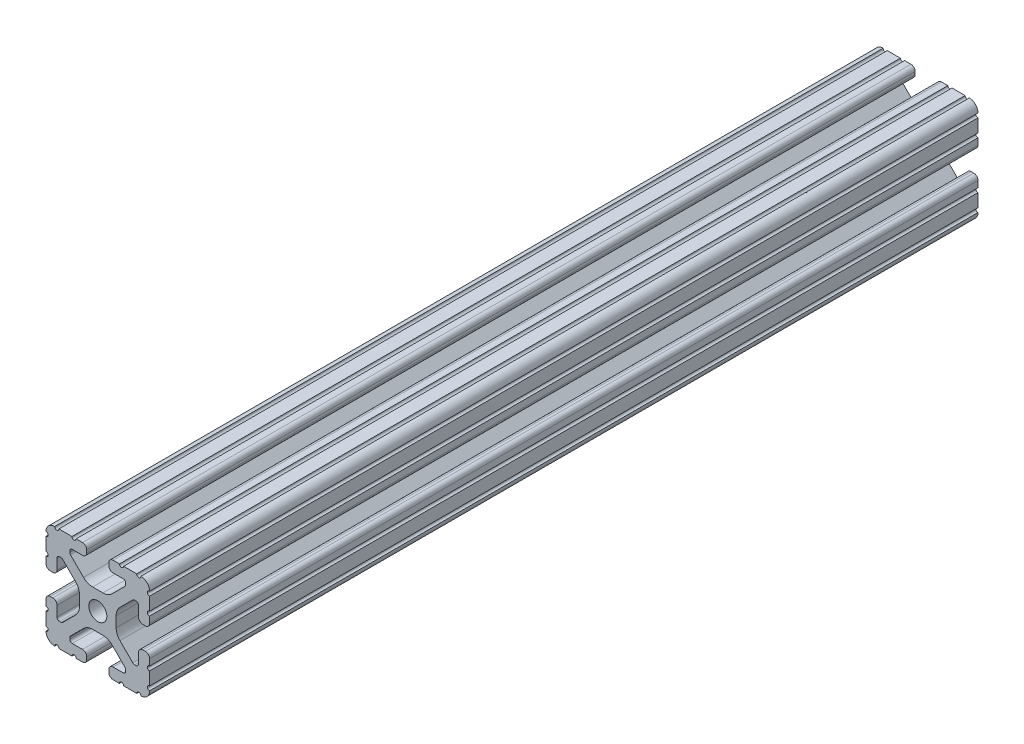
SolidWorks part; units mm, degrees
ref_plane "Front Plane" through (0, 0, 0) normal (0, 0, 1) x (1, 0, 0)
ref_plane "Top Plane" through (0, 0, 0) normal (0, 1, 0) x (1, 0, 0)
ref_plane "Right Plane" through (0, 0, 0) normal (1, 0, 0) x (0, 0, -1)
sketch "Sketch1" plane through (0, 0, 0) normal (0, 0, 1) x (1, 0, 0)
  line L0 (-10.287, 13.5524) -> (-10.287, 14.0843)
  line L1 (-9.3853, 14.986) -> (-5.6176, 14.986)
  line L2 (-4.064, 16.5396) -> (-4.064, 17.4964)
  line L3 (-5.6176, 19.05) -> (-7.9742, 19.05)
  line L4 (-9.4982, 19.05) -> (-14.3277, 19.05)
  line L5 (-19.05, 14.3277) -> (-19.05, 9.4961)
  line L6 (-19.05, 7.9763) -> (-19.05, 5.6176)
  line L7 (-17.4964, 4.064) -> (-16.5396, 4.064)
  line L8 (-14.986, 5.6176) -> (-14.986, 9.3853)
  line L9 (-14.0843, 10.287) -> (-13.516, 10.287)
  line L10 (-12.8784, 10.0229) -> (-8.1476, 5.2921)
  line L11 (-6.7564, 1.9335) -> (-6.7564, -1.9335)
  line L12 (-8.1476, -5.2921) -> (-12.8784, -10.0229)
  line L13 (-13.516, -10.287) -> (-14.0843, -10.287)
  line L14 (-14.986, -9.3853) -> (-14.986, -5.6176)
  line L15 (-16.5396, -4.064) -> (-17.4964, -4.064)
  line L16 (-19.05, -5.6176) -> (-19.05, -7.9763)
  line L17 (-19.05, -9.4961) -> (-19.05, -14.3277)
  line L18 (-14.3277, -19.05) -> (-9.4961, -19.05)
  line L19 (-7.9763, -19.05) -> (-5.6176, -19.05)
  line L20 (-4.064, -17.4964) -> (-4.064, -16.5396)
  line L21 (-5.6176, -14.986) -> (-9.3853, -14.986)
  line L22 (-10.287, -14.0843) -> (-10.287, -13.5524)
  line L23 (-10.0229, -12.9148) -> (-5.2522, -8.144)
  line L24 (-1.9022, -6.7564) -> (1.9022, -6.7564)
  line L25 (5.2522, -8.144) -> (10.0229, -12.9148)
  line L26 (10.287, -13.5524) -> (10.287, -14.0843)
  line L27 (9.3853, -14.986) -> (5.6176, -14.986)
  line L28 (4.064, -16.5396) -> (4.064, -17.4964)
  line L29 (5.6176, -19.05) -> (7.9763, -19.05)
  line L30 (9.4961, -19.05) -> (14.3277, -19.05)
  line L31 (19.05, -14.3277) -> (19.05, -9.4961)
  line L32 (19.05, -7.9763) -> (19.05, -5.6176)
  line L33 (17.4964, -4.064) -> (16.5396, -4.064)
  line L34 (14.986, -5.6176) -> (14.986, -9.3853)
  line L35 (14.0843, -10.287) -> (13.516, -10.287)
  line L36 (12.8784, -10.0229) -> (8.1476, -5.2921)
  line L37 (6.7564, -1.9335) -> (6.7564, 1.9335)
  line L38 (8.1476, 5.2921) -> (12.8784, 10.0229)
  line L39 (13.516, 10.287) -> (14.0843, 10.287)
  line L40 (14.986, 9.3853) -> (14.986, 5.6176)
  line L41 (16.5396, 4.064) -> (17.4964, 4.064)
  line L42 (19.05, 5.6176) -> (19.05, 7.9763)
  line L43 (19.05, 9.4961) -> (19.05, 14.3277)
  line L44 (14.3277, 19.05) -> (9.4982, 19.05)
  line L45 (7.9742, 19.05) -> (5.6176, 19.05)
  line L46 (4.064, 17.4964) -> (4.064, 16.5396)
  line L47 (5.6176, 14.986) -> (9.3853, 14.986)
  line L48 (10.287, 14.0843) -> (10.287, 13.5524)
  line L49 (10.0229, 12.9148) -> (5.2522, 8.144)
  line L50 (1.9022, 6.7564) -> (-1.9022, 6.7564)
  line L51 (-5.2522, 8.144) -> (-10.0229, 12.9148)
  circle A0 centre (0, 0) radius 3.3274
  arc A1 (-9.3853, 14.986) -> (-10.287, 14.0843) centre (-9.3853, 14.0843) ccw
  arc A2 (-5.6176, 14.986) -> (-4.064, 16.5396) centre (-5.6176, 16.5396) ccw
  arc A3 (-4.064, 17.4964) -> (-5.6176, 19.05) centre (-5.6176, 17.4964) ccw
  arc A4 (-9.4982, 19.05) -> (-7.9742, 19.05) centre (-8.7362, 19.05) ccw
  arc A5 (-15.8475, 19.05) -> (-14.3277, 19.05) centre (-15.0876, 18.9933) ccw
  arc A6 (-15.8475, 19.05) -> (-19.05, 15.8475) centre (-15.8751, 15.8751) ccw
  arc A7 (-19.05, 14.3277) -> (-19.05, 15.8475) centre (-18.9933, 15.0876) ccw
  arc A8 (-19.05, 7.9763) -> (-19.05, 9.4961) centre (-18.9933, 8.7362) ccw
  arc A9 (-19.05, 5.6176) -> (-17.4964, 4.064) centre (-17.4964, 5.6176) ccw
  arc A10 (-16.5396, 4.064) -> (-14.986, 5.6176) centre (-16.5396, 5.6176) ccw
  arc A11 (-14.0843, 10.287) -> (-14.986, 9.3853) centre (-14.0843, 9.3853) ccw
  arc A12 (-12.8784, 10.0229) -> (-13.516, 10.287) centre (-13.516, 9.3853) ccw
  arc A13 (-6.7564, 1.9335) -> (-8.1476, 5.2921) centre (-11.5062, 1.9335) ccw
  arc A14 (-8.1476, -5.2921) -> (-6.7564, -1.9335) centre (-11.5062, -1.9335) ccw
  arc A15 (-13.516, -10.287) -> (-12.8784, -10.0229) centre (-13.516, -9.3853) ccw
  arc A16 (-14.986, -9.3853) -> (-14.0843, -10.287) centre (-14.0843, -9.3853) ccw
  arc A17 (-14.986, -5.6176) -> (-16.5396, -4.064) centre (-16.5396, -5.6176) ccw
  arc A18 (-17.4964, -4.064) -> (-19.05, -5.6176) centre (-17.4964, -5.6176) ccw
  arc A19 (-19.05, -9.4961) -> (-19.05, -7.9763) centre (-18.9933, -8.7362) ccw
  arc A20 (-19.05, -15.8475) -> (-19.05, -14.3277) centre (-18.9933, -15.0876) ccw
  arc A21 (-19.05, -15.8475) -> (-15.8475, -19.05) centre (-15.8751, -15.8751) ccw
  arc A22 (-14.3277, -19.05) -> (-15.8475, -19.05) centre (-15.0876, -18.9933) ccw
  arc A23 (-7.9763, -19.05) -> (-9.4961, -19.05) centre (-8.7362, -18.9933) ccw
  arc A24 (-5.6176, -19.05) -> (-4.064, -17.4964) centre (-5.6176, -17.4964) ccw
  arc A25 (-4.064, -16.5396) -> (-5.6176, -14.986) centre (-5.6176, -16.5396) ccw
  arc A26 (-10.287, -14.0843) -> (-9.3853, -14.986) centre (-9.3853, -14.0843) ccw
  arc A27 (-10.0229, -12.9148) -> (-10.287, -13.5524) centre (-9.3853, -13.5524) ccw
  arc A28 (-1.9022, -6.7564) -> (-5.2522, -8.144) centre (-1.9022, -11.494) ccw
  arc A29 (5.2522, -8.144) -> (1.9022, -6.7564) centre (1.9022, -11.494) ccw
  arc A30 (10.287, -13.5524) -> (10.0229, -12.9148) centre (9.3853, -13.5524) ccw
  arc A31 (9.3853, -14.986) -> (10.287, -14.0843) centre (9.3853, -14.0843) ccw
  arc A32 (5.6176, -14.986) -> (4.064, -16.5396) centre (5.6176, -16.5396) ccw
  arc A33 (4.064, -17.4964) -> (5.6176, -19.05) centre (5.6176, -17.4964) ccw
  arc A34 (9.4961, -19.05) -> (7.9763, -19.05) centre (8.7362, -18.9933) ccw
  arc A35 (15.8475, -19.05) -> (14.3277, -19.05) centre (15.0876, -18.9933) ccw
  arc A36 (15.8475, -19.05) -> (19.05, -15.8475) centre (15.8751, -15.8751) ccw
  arc A37 (19.05, -14.3277) -> (19.05, -15.8475) centre (18.9933, -15.0876) ccw
  arc A38 (19.05, -7.9763) -> (19.05, -9.4961) centre (18.9933, -8.7362) ccw
  arc A39 (19.05, -5.6176) -> (17.4964, -4.064) centre (17.4964, -5.6176) ccw
  arc A40 (16.5396, -4.064) -> (14.986, -5.6176) centre (16.5396, -5.6176) ccw
  arc A41 (14.0843, -10.287) -> (14.986, -9.3853) centre (14.0843, -9.3853) ccw
  arc A42 (12.8784, -10.0229) -> (13.516, -10.287) centre (13.516, -9.3853) ccw
  arc A43 (6.7564, -1.9335) -> (8.1476, -5.2921) centre (11.5062, -1.9335) ccw
  arc A44 (8.1476, 5.2921) -> (6.7564, 1.9335) centre (11.5062, 1.9335) ccw
  arc A45 (13.516, 10.287) -> (12.8784, 10.0229) centre (13.516, 9.3853) ccw
  arc A46 (14.986, 9.3853) -> (14.0843, 10.287) centre (14.0843, 9.3853) ccw
  arc A47 (14.986, 5.6176) -> (16.5396, 4.064) centre (16.5396, 5.6176) ccw
  arc A48 (17.4964, 4.064) -> (19.05, 5.6176) centre (17.4964, 5.6176) ccw
  arc A49 (19.05, 9.4961) -> (19.05, 7.9763) centre (18.9933, 8.7362) ccw
  arc A50 (19.05, 15.8475) -> (19.05, 14.3277) centre (18.9933, 15.0876) ccw
  arc A51 (19.05, 15.8475) -> (15.8475, 19.05) centre (15.8751, 15.8751) ccw
  arc A52 (14.3277, 19.05) -> (15.8475, 19.05) centre (15.0876, 18.9933) ccw
  arc A53 (7.9742, 19.05) -> (9.4982, 19.05) centre (8.7362, 19.05) ccw
  arc A54 (5.6176, 19.05) -> (4.064, 17.4964) centre (5.6176, 17.4964) ccw
  arc A55 (4.064, 16.5396) -> (5.6176, 14.986) centre (5.6176, 16.5396) ccw
  arc A56 (10.287, 14.0843) -> (9.3853, 14.986) centre (9.3853, 14.0843) ccw
  arc A57 (10.0229, 12.9148) -> (10.287, 13.5524) centre (9.3853, 13.5524) ccw
  arc A58 (1.9022, 6.7564) -> (5.2522, 8.144) centre (1.9022, 11.494) ccw
  arc A59 (-5.2522, 8.144) -> (-1.9022, 6.7564) centre (-1.9022, 11.494) ccw
  arc A60 (-10.287, 13.5524) -> (-10.0229, 12.9148) centre (-9.3853, 13.5524) ccw
extrude "Boss-Extrude1" add sketch "Sketch1" along normal mid plane 304.8
